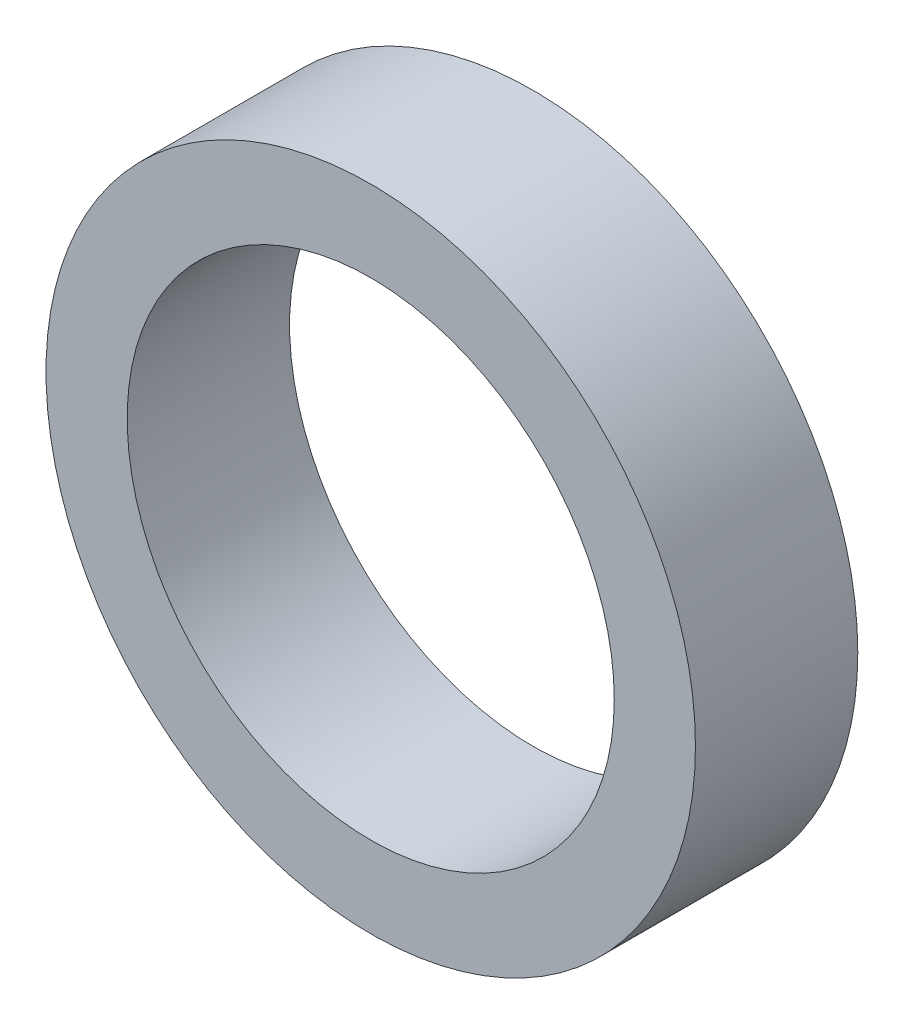
SolidWorks part; units mm, degrees
ref_plane "前视基准面" through (0, 0, 0) normal (0, 0, 1) x (1, 0, 0)
ref_plane "上视基准面" through (0, 0, 0) normal (0, 1, 0) x (1, 0, 0)
ref_plane "右视基准面" through (0, 0, 0) normal (1, 0, 0) x (0, 0, -1)
other "Configuration Table"
sketch "草图1" plane through (0, 0, 0) normal (0, 0, 1) x (1, 0, 0)
  circle A0 centre (0, 0) radius 3
  circle A1 centre (0, 0) radius 4
  dimension "D1" = 6
  dimension "D2" = 8
extrude "凸台-拉伸1" add sketch "草图1" along normal blind 2
